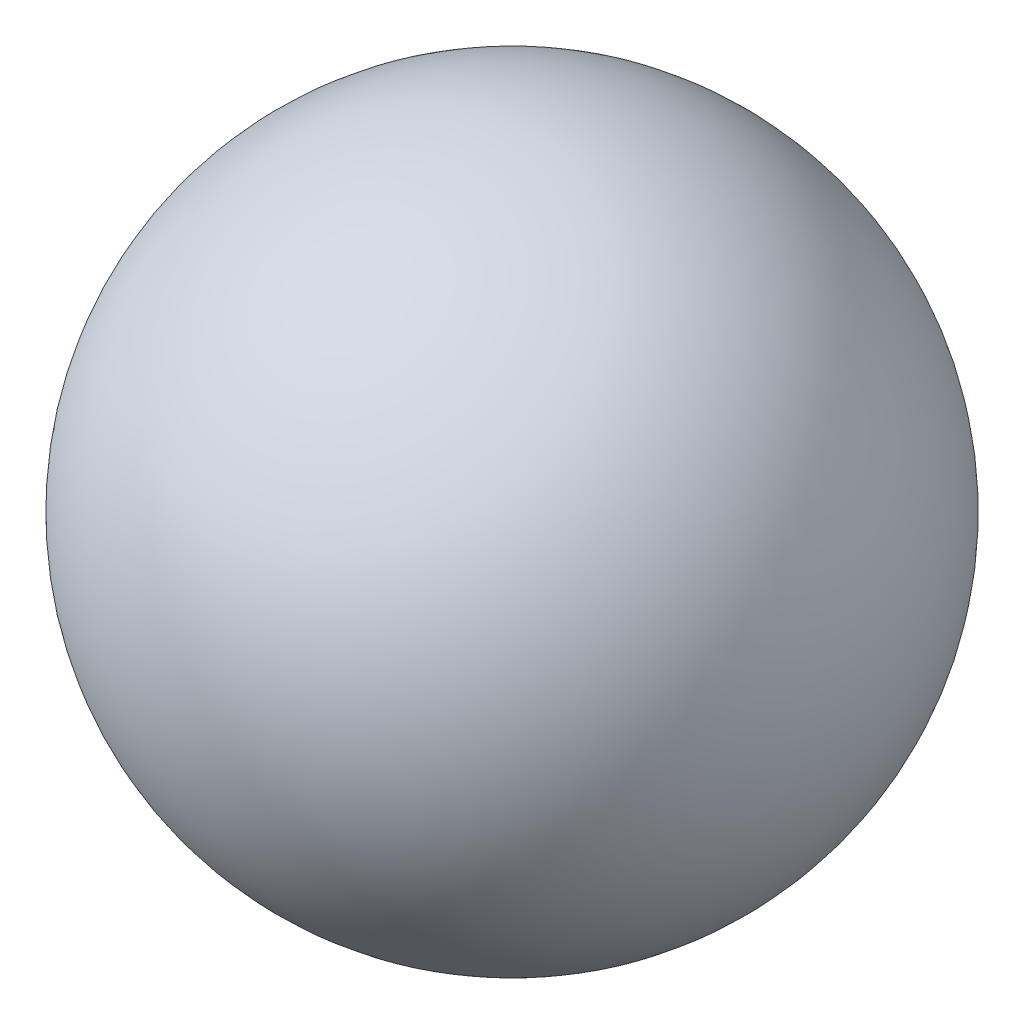
SolidWorks part; units mm, degrees
ref_plane "Front" through (0, 0, 0) normal (0, 0, 1) x (1, 0, 0)
ref_plane "Top" through (0, 0, 0) normal (0, 1, 0) x (1, 0, 0)
ref_plane "Right" through (0, 0, 0) normal (1, 0, 0) x (0, 0, -1)
sketch "Croquis1" plane through (0, 0, 0) normal (1, 0, 0) x (0, 0, -1)
  line L0 (0, -8.15) -> (0, 8.15)
  arc A0 (0, -8.15) -> (0, 8.15) centre (0, 0) cw
  point P4 (0, 0)
  dimension "D1" = 16.3
revolve "Revolución1" add sketch "Croquis1" angle 360 about L0
